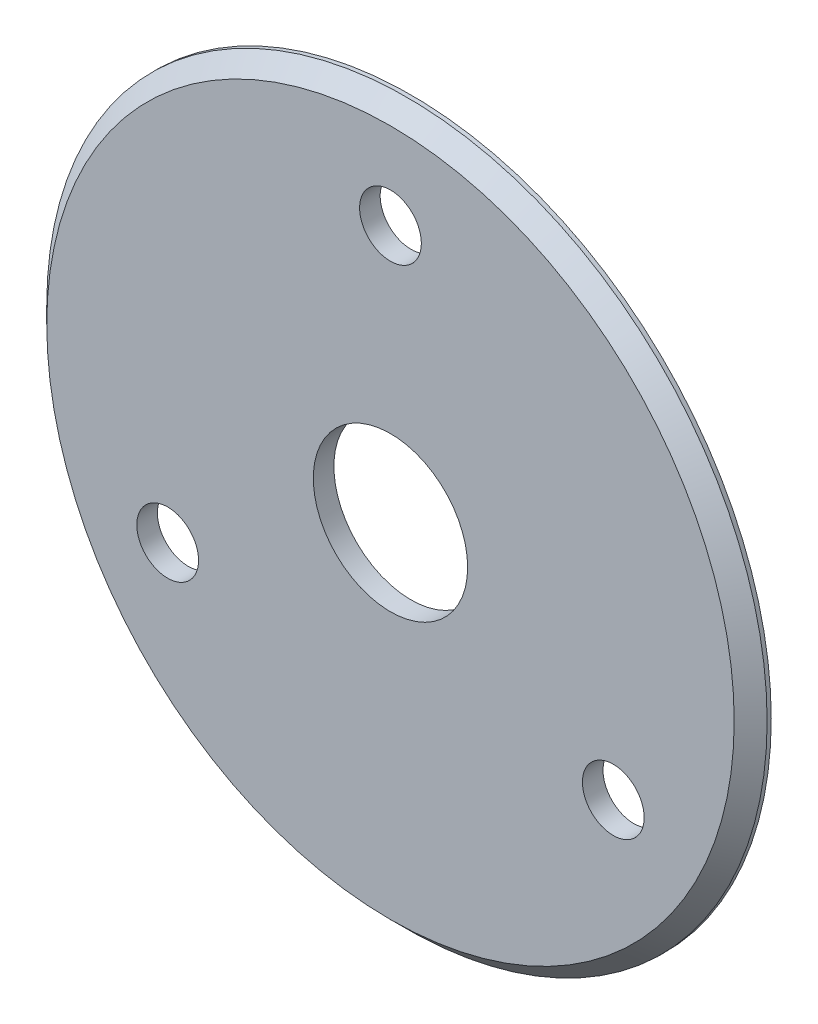
SolidWorks part; units mm, degrees
ref_plane "Front Plane" through (0, 0, 0) normal (0, 0, 1) x (1, 0, 0)
ref_plane "Top Plane" through (0, 0, 0) normal (0, 1, 0) x (1, 0, 0)
ref_plane "Right Plane" through (0, 0, 0) normal (1, 0, 0) x (0, 0, -1)
sketch "Sketch1" plane through (0, 0, 0) normal (0, 0, 1) x (1, 0, 0)
  circle A0 centre (0, 0) radius 35
  circle A1 centre (0, 0) radius 7.5
  circle A2 centre (0, 25) radius 3
  circle A3 centre (21.6506, -12.5) radius 3
  circle A4 centre (-21.6506, -12.5) radius 3
  point P13 (0, 0)
  dimension "D1" = 70
  dimension "D2" = 15
  dimension "D4" = 6
  dimension "D3" = 25
extrude "Boss-Extrude1" add sketch "Sketch1" along normal blind 2
chamfer "Chamfer1" distance 1.6 angle 45 1 edges at (35, 0, 2)
